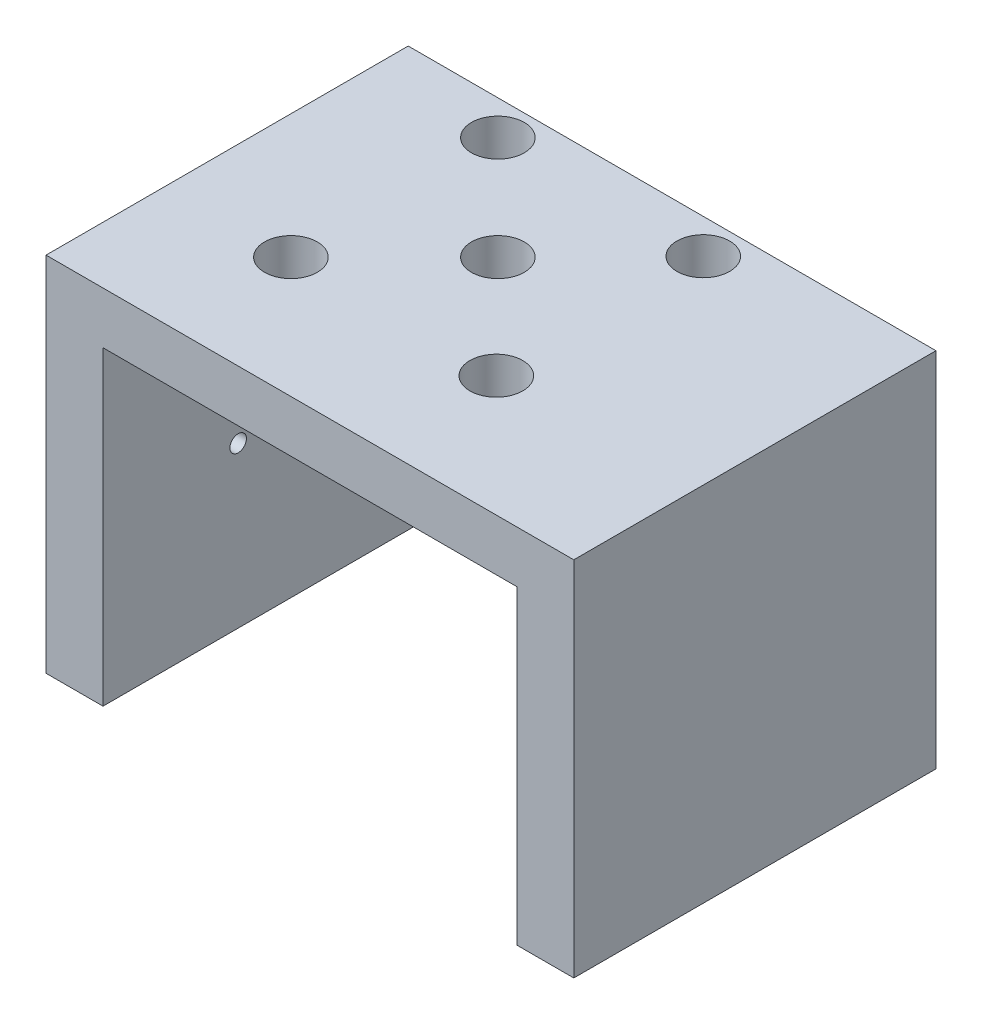
SolidWorks part; units mm, degrees
ref_plane "Front Plane" through (0, 0, 0) normal (0, 0, 1) x (1, 0, 0)
ref_plane "Top Plane" through (0, 0, 0) normal (0, 1, 0) x (1, 0, 0)
ref_plane "Right Plane" through (0, 0, 0) normal (1, 0, 0) x (0, 0, -1)
sketch "Sketch1" plane through (0, 0, 0) normal (0, 0, 1) x (1, 0, 0)
  line L0 (-51, 0) -> (-45.4951, 0)
  line L1 (0, 0) -> (-5.4951, 0)
  line L2 (0, 0) -> (0, 35)
  line L3 (0, 35) -> (-51, 35)
  line L4 (-51, 0) -> (-51, 35)
  line L5 (-45.4951, 0) -> (-45.4951, 30)
  line L6 (-45.4951, 30) -> (-5.4951, 30)
  line L7 (-5.4951, 30) -> (-5.4951, 0)
  line L8 (-45.4951, 0) -> (-51, 0)
  dimension "D1" = 30
  dimension "35m" = 35
  dimension "46" = 51
  dimension "D2" = 40
  dimension "D3" = 5.5049
extrude "Boss-Extrude1" add sketch "Sketch1" against normal blind 35 contours L6 L7 L1 L2 L3 L4 L0 L5
sketch "Sketch2" plane through (-51, 0, 0) normal (-1, 0, 0) x (0, 0, 1)
  line L0 (-17.5633, 15.4747) -> (-13.0633, 15.4747)
  line L1 (-17.5633, 15.4747) -> (-22.0633, 15.4747)
  circle A0 centre (-17.5633, 15.4747) radius 2
  circle A1 centre (-17.5633, 15.4747) radius 15
  circle A2 centre (-13.0633, 15.4747) radius 0.8
  circle A3 centre (-22.0633, 15.4747) radius 0.8
  dimension "D1" = 30
  dimension "D2" = 4
  dimension "D3" = 1.6
  dimension "1" = 1.6
extrude "Cut-Extrude1" cut sketch "Sketch2" against normal blind 6
sketch "Sketch3" plane through (0, 35, 0) normal (0, 1, 0) x (1, 0, 0)
  line L0 (-51, 31.6638) -> (-39, 31.6638)
  line L1 (-51, 35) -> (-51, 0) construction
  line L2 (-39, 31.6638) -> (-39, 11.6638)
  line L3 (-39, 31.6638) -> (-19.15, 31.6638)
  line L4 (-39, 11.6638) -> (-19.15, 11.6638)
  line L5 (-39, 21.6638) -> (-29, 21.6638)
  circle A0 centre (-39, 31.6638) radius 2.55
  circle A1 centre (-39, 11.6638) radius 2.55
  circle A2 centre (-19.15, 31.6638) radius 2.55
  circle A3 centre (-19.15, 11.6638) radius 2.55
  circle A4 centre (-29, 21.6638) radius 2.55
  dimension "D1" = 5.1
  dimension "D2" = 5.1
  dimension "5." = 5.1
  dimension "D3" = 5.1
  dimension "D4" = 5.1
extrude "Cut-Extrude2" cut sketch "Sketch3" against normal blind 6 contours A3 | A2 | A1 | A4 | A0
